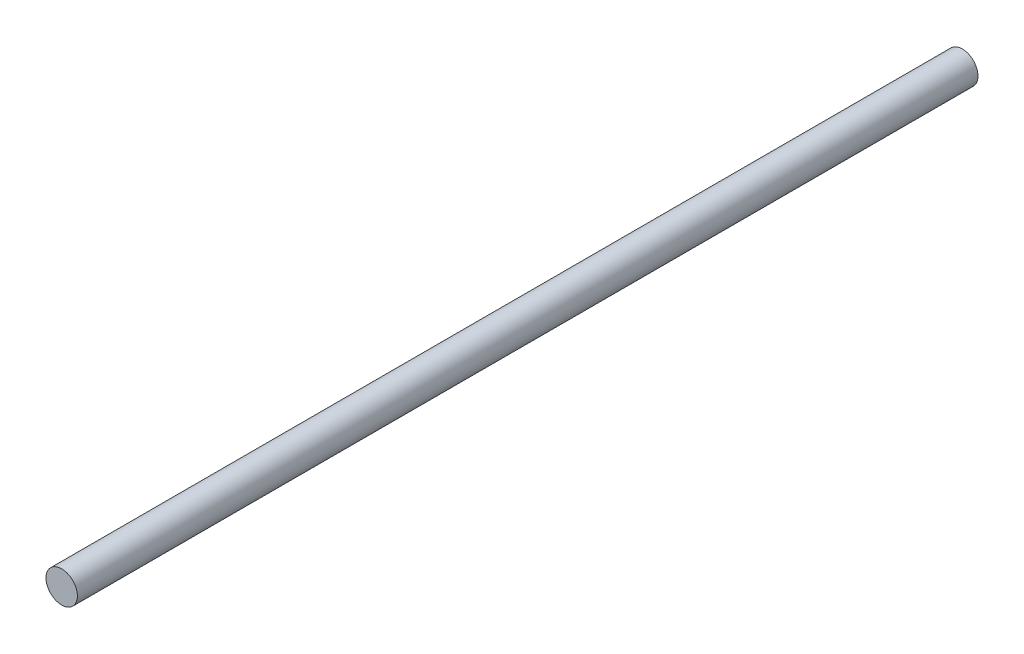
SolidWorks part; units mm, degrees
material "Plain Carbon Steel"
ref_plane "Front Plane" through (0, 0, 0) normal (0, 0, 1) x (1, 0, 0)
ref_plane "Top Plane" through (0, 0, 0) normal (0, 1, 0) x (1, 0, 0)
ref_plane "Right Plane" through (0, 0, 0) normal (1, 0, 0) x (0, 0, -1)
sketch "Sketch1" plane through (0, 0, 0) normal (0, 0, 1) x (1, 0, 0)
  circle A0 centre (0, 0) radius 3.175
  dimension "D1" = 6.35
extrude "Boss-Extrude1" add sketch "Sketch1" along normal mid plane 182
